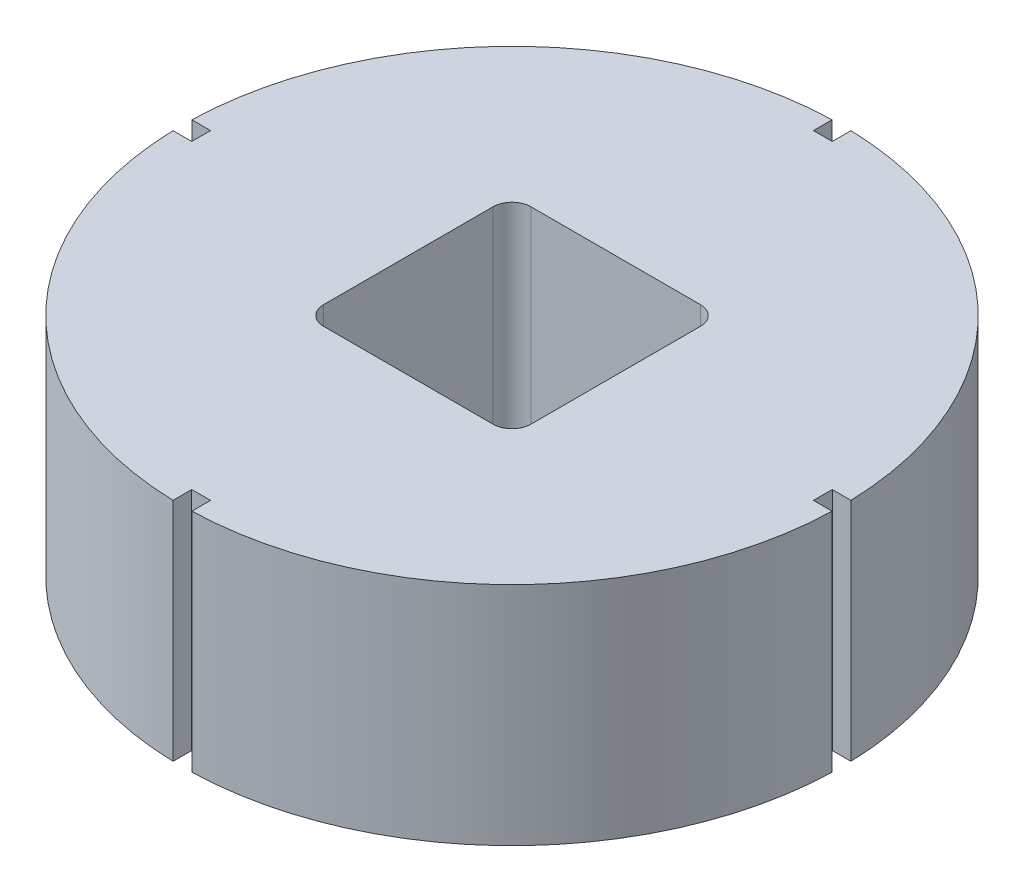
SolidWorks part; units mm, degrees
ref_plane "Front Plane" through (0, 0, 0) normal (0, 0, 1) x (1, 0, 0)
ref_plane "Top Plane" through (0, 0, 0) normal (0, 1, 0) x (1, 0, 0)
ref_plane "Right Plane" through (0, 0, 0) normal (1, 0, 0) x (0, 0, -1)
sketch "Sketch1" plane through (0, 0, 0) normal (0, 1, 0) x (1, 0, 0)
  circle A0 centre (0, 0) radius 35
  dimension "D1" = 70
extrude "Boss-Extrude1" add sketch "Sketch1" along normal blind 24
sketch "Sketch2" plane through (0, 0, 0) normal (0, -1, 0) x (1, 0, 0)
  circle A0 centre (0, 0) radius 10
  dimension "D1" = 20
extrude "Boss-Extrude2" add sketch "Sketch2" along normal blind 5
sketch "Sketch3" plane through (0, 24, 0) normal (0, 1, 0) x (1, 0, 0)
  line L1 (-9, 11) -> (9, 11)
  line L2 (-11, 9) -> (-11, -9)
  line L3 (-9, -11) -> (9, -11)
  line L4 (11, 9) -> (11, -9)
  line L5 (-11, 11) -> (11, -11) construction
  line L6 (-11, -11) -> (11, 11) construction
  arc A0 (-11, -9) -> (-9, -11) centre (-9, -9) ccw
  arc A1 (9, -11) -> (11, -9) centre (9, -9) ccw
  arc A2 (9, 11) -> (11, 9) centre (9, 9) cw
  arc A3 (-9, 11) -> (-11, 9) centre (-9, 9) ccw
  point P0 (0, 0)
  dimension "D3" = 2
  dimension "D1" = 22
  dimension "D2" = 22
extrude "Cut-Extrude1" cut sketch "Sketch3" against normal blind 25
sketch "Sketch4" plane through (0, 24, 0) normal (0, 1, 0) x (1, 0, 0)
  line L0 (0, 35) -> (0, -35) construction
  line L1 (-1, 34.9857) -> (-1, 33)
  line L2 (-1, 33) -> (1, 33)
  line L3 (1, 33) -> (1, 34.9857)
  line L4 (34.9857, 1) -> (33, 1)
  line L5 (33, 1) -> (33, -1)
  line L6 (33, -1) -> (34.9857, -1)
  line L7 (1, -34.9857) -> (1, -33)
  line L8 (1, -33) -> (-1, -33)
  line L9 (-1, -33) -> (-1, -34.9857)
  line L10 (-34.9857, -1) -> (-33, -1)
  line L11 (-33, -1) -> (-33, 1)
  line L12 (-33, 1) -> (-34.9857, 1)
  circle A0 centre (0, 0) radius 35 construction
  arc A1 (1, 34.9857) -> (-1, 34.9857) centre (0, 0) ccw
  arc A2 (34.9857, -1) -> (34.9857, 1) centre (0, 0) ccw
  arc A3 (-1, -34.9857) -> (1, -34.9857) centre (0, 0) ccw
  arc A4 (-34.9857, 1) -> (-34.9857, -1) centre (0, 0) ccw
  point P24 (0, 0)
  dimension "D1" = 1
  dimension "D2" = 1
  dimension "D3" = 2
  dimension "D4" = 4
extrude "Cut-Extrude2" cut sketch "Sketch4" against normal blind 36
